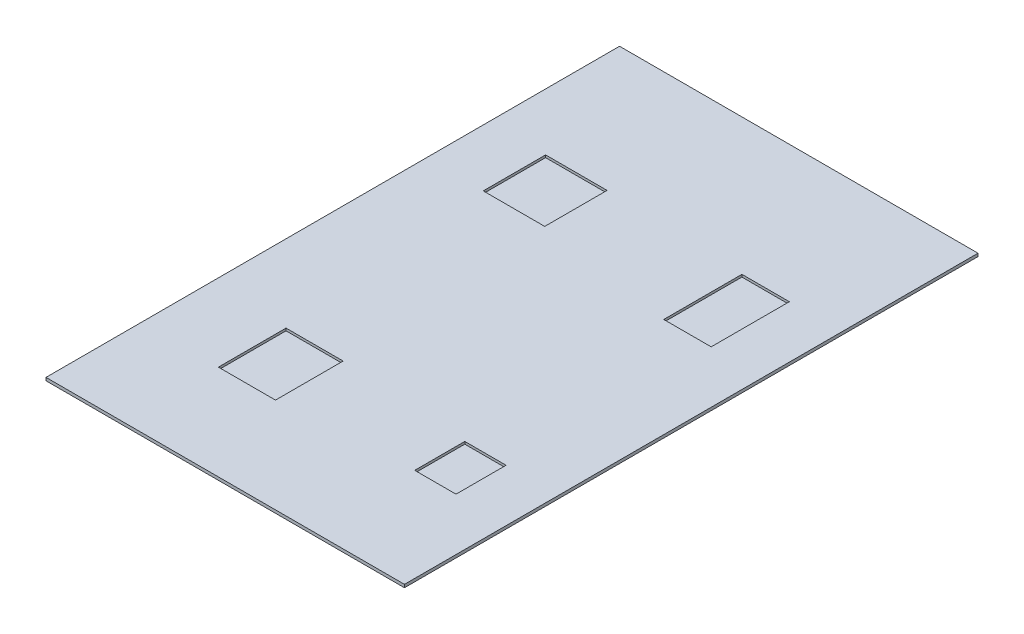
SolidWorks part; units mm, degrees
ref_plane "Front Plane" through (0, 0, 0) normal (0, 0, 1) x (1, 0, 0)
ref_plane "Top Plane" through (0, 0, 0) normal (0, 1, 0) x (1, 0, 0)
ref_plane "Right Plane" through (0, 0, 0) normal (1, 0, 0) x (0, 0, -1)
sketch "Sketch1" plane through (0, 0, 0) normal (0, 1, 0) x (1, 0, 0)
  line L1 (-190.5, -304.8) -> (190.5, -304.8)
  line L2 (-190.5, -304.8) -> (-190.5, 304.8)
  line L3 (-190.5, 304.8) -> (190.5, 304.8)
  line L4 (190.5, -304.8) -> (190.5, 304.8)
  line L5 (0, 304.8) -> (0, -304.8) construction
  line L6 (-190.5, 0) -> (190.5, 0) construction
  point P0 (0, 0)
  dimension "D1" = 381
  dimension "D2" = 609.6
extrude "Boss-Extrude1" add sketch "Sketch1" along normal blind 3.175
sketch "Sketch2" plane through (0, 3.175, 0) normal (0, 1, 0) x (1, 0, 0)
  line L1 (-129.7725, 99.1966) -> (-64.4194, 99.1966)
  line L2 (-129.7725, 99.1966) -> (-129.7725, 165.4833)
  line L3 (-129.7725, 165.4833) -> (-64.4194, 165.4833)
  line L4 (-64.4194, 99.1966) -> (-64.4194, 165.4833)
  line L5 (-97.096, 165.4833) -> (-97.096, 99.1966) construction
  line L6 (-129.7725, 132.3399) -> (-64.4194, 132.3399) construction
  line L7 (84.4922, 76.7898) -> (134.9074, 76.7898)
  line L8 (84.4922, 76.7898) -> (84.4922, 159.8816)
  line L9 (84.4922, 159.8816) -> (134.9074, 159.8816)
  line L10 (134.9074, 76.7898) -> (134.9074, 159.8816)
  line L11 (109.6998, 159.8816) -> (109.6998, 76.7898) construction
  line L12 (84.4922, 118.3357) -> (134.9074, 118.3357) construction
  line L13 (-108.2994, -203.7615) -> (-47.6144, -203.7615)
  line L14 (-108.2994, -203.7615) -> (-108.2994, -131.8731)
  line L15 (-108.2994, -131.8731) -> (-47.6144, -131.8731)
  line L16 (-47.6144, -203.7615) -> (-47.6144, -131.8731)
  line L17 (-77.9569, -131.8731) -> (-77.9569, -203.7615) construction
  line L18 (-108.2994, -167.8173) -> (-47.6144, -167.8173) construction
  line L19 (91.0275, -194.4253) -> (134.9074, -194.4253)
  line L20 (91.0275, -194.4253) -> (91.0275, -141.2093)
  line L21 (91.0275, -141.2093) -> (134.9074, -141.2093)
  line L22 (134.9074, -194.4253) -> (134.9074, -141.2093)
  line L23 (112.9674, -141.2093) -> (112.9674, -194.4253) construction
  line L24 (91.0275, -167.8173) -> (134.9074, -167.8173) construction
  point P0 (-97.096, 132.3399)
  point P4 (109.6998, 118.3357)
  point P8 (-77.9569, -167.8173)
  point P12 (112.9674, -167.8173)
extrude "Cut-Extrude1" cut sketch "Sketch2" against normal blind 2.54
